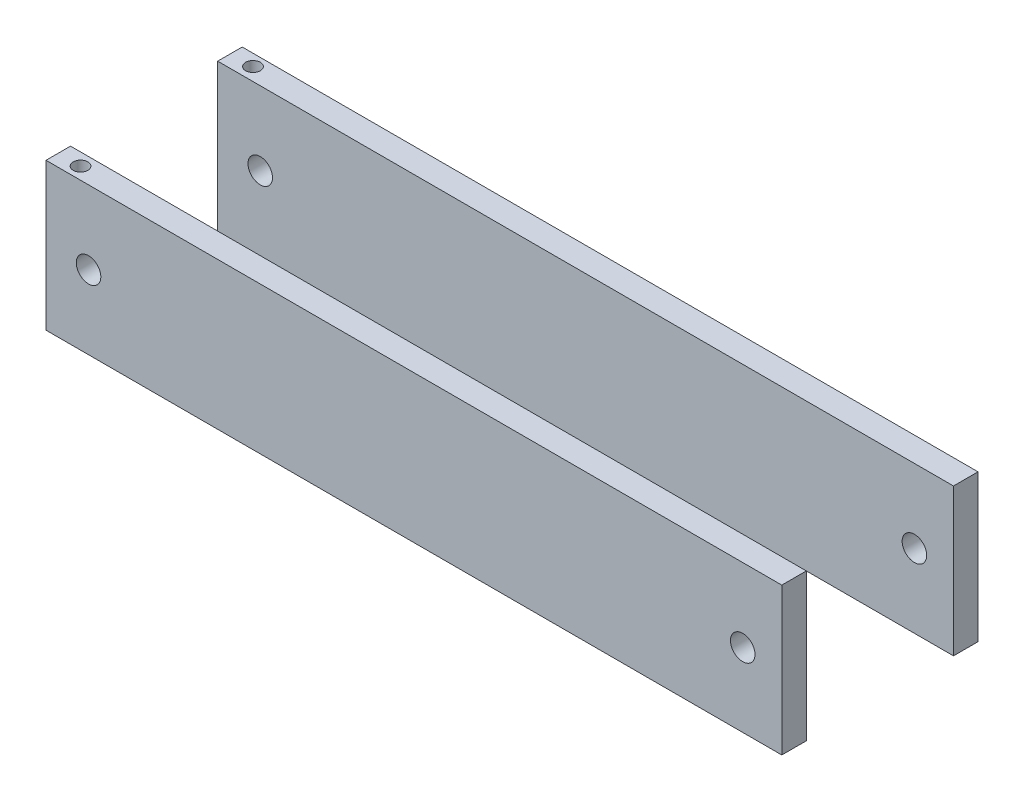
SolidWorks part; units mm, degrees
ref_plane "Front Plane" through (0, 0, 0) normal (0, 0, 1) x (1, 0, 0)
ref_plane "Top Plane" through (0, 0, 0) normal (0, 1, 0) x (1, 0, 0)
ref_plane "Right Plane" through (0, 0, 0) normal (1, 0, 0) x (0, 0, -1)
sketch "Sketch1" plane through (0, 0, 0) normal (0, 0, 1) x (1, 0, 0)
  line L1 (-150, 30) -> (150, 30)
  line L2 (-150, 30) -> (-150, -30)
  line L3 (-150, -30) -> (150, -30)
  line L4 (150, 30) -> (150, -30)
  line L5 (-150, 30) -> (150, -30) construction
  line L6 (-150, -30) -> (150, 30) construction
  point P0 (0, 0)
  dimension "D1" = 300
  dimension "D2" = 60
extrude "Boss-Extrude1" add sketch "Sketch1" along normal mid plane 80
sketch "Sketch2" plane through (0, 30, 0) normal (0, 1, 0) x (1, 0, 0)
  line L0 (150, -40) -> (150, 40) construction
  line L1 (-150, 30) -> (150, 30)
  line L2 (-150, 30) -> (-150, -30)
  line L3 (-150, -30) -> (150, -30)
  line L4 (150, 30) -> (150, -30)
  line L5 (-150, 30) -> (150, -30) construction
  line L6 (-150, -30) -> (150, 30) construction
  point P0 (0, 0)
  dimension "D1" = 60
extrude "Cut-Extrude2" cut sketch "Sketch2" against normal through all
sketch "Sketch5" plane through (0, 0, -40) normal (0, 0, -1) x (-1, 0, 0)
  circle A0 centre (-134.0729, 0) radius 5
  circle A1 centre (132.6496, 0) radius 5
  dimension "D1" = 10
  dimension "D2" = 10
extrude "Cut-Extrude3" cut sketch "Sketch5" against normal through all
sketch "Sketch7" plane through (0, 30, 0) normal (0, 1, 0) x (1, 0, 0)
  circle A0 centre (-140.9046, -35.0127) radius 3
  circle A1 centre (-140.9046, 35.2973) radius 3
  dimension "D1" = 70.31
extrude "Cut-Extrude4" cut sketch "Sketch7" against normal blind 10
